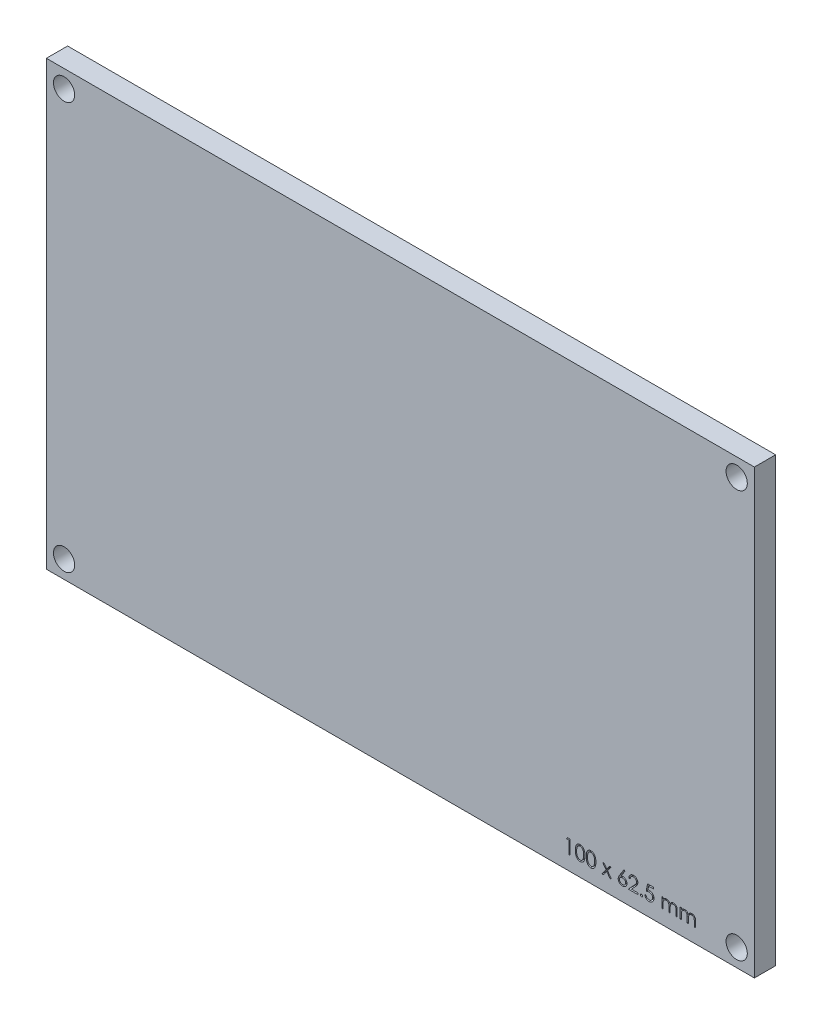
SolidWorks part; units mm, degrees
ref_plane "Front Plane" through (0, 0, 0) normal (0, 0, 1) x (1, 0, 0)
ref_plane "Top Plane" through (0, 0, 0) normal (0, 1, 0) x (1, 0, 0)
ref_plane "Right Plane" through (0, 0, 0) normal (1, 0, 0) x (0, 0, -1)
sketch "Sketch1" plane through (0, 0, 0) normal (0, 0, 1) x (1, 0, 0)
  line L1 (-50, 31.25) -> (50, 31.25)
  line L2 (-50, 31.25) -> (-50, -31.25)
  line L3 (-50, -31.25) -> (50, -31.25)
  line L4 (50, 31.25) -> (50, -31.25)
  line L5 (-50, 31.25) -> (50, -31.25) construction
  line L6 (-50, -31.25) -> (50, 31.25) construction
  point P5 (0, 0)
  point P6 (0, 0)
  point P8 (0, 0)
  point P9 (-8.951, -1.6898)
  dimension "D1" = 62.5
  dimension "D2" = 100
  dimension "D3" = 31.25
  dimension "D4" = 50
extrude "Boss-Extrude1" add sketch "Sketch1" along normal blind 3 contours L1 L4 L3 L2
sketch "Sketch2" plane through (0, 0, 3) normal (0, 0, 1) x (1, 0, 0)
  line L0 (1.65, 0) -> (-1.65, 0) construction
  line L2 (0, -1.65) -> (0, 1.65) construction
  line L7 (-50, 31.25) -> (50, 31.25) construction
  line L9 (-50, 31.25) -> (-50, -31.25) construction
  circle A0 centre (-47.5, 28.75) radius 1.5
  circle A1 centre (-47.5, -28.75) radius 1.5
  circle A2 centre (47.5, -28.75) radius 1.5
  circle A3 centre (47.5, 28.75) radius 1.5
  dimension "D1" = 3
  dimension "D2" = 1
  dimension "D3" = 1
extrude "Cut-Extrude1" cut sketch "Sketch2" against normal through all both and the other way through all contours A0 | A1 | A3 | A2
sketch "Sketch4" plane through (0, 0, 3) normal (0, 0, 1) x (1, 0, 0)
  text T0 "100 x 62.5 mm\r\n" font "Century Gothic" height 2
extrude "Cut-Extrude2" cut sketch "Sketch4" against normal blind 1
